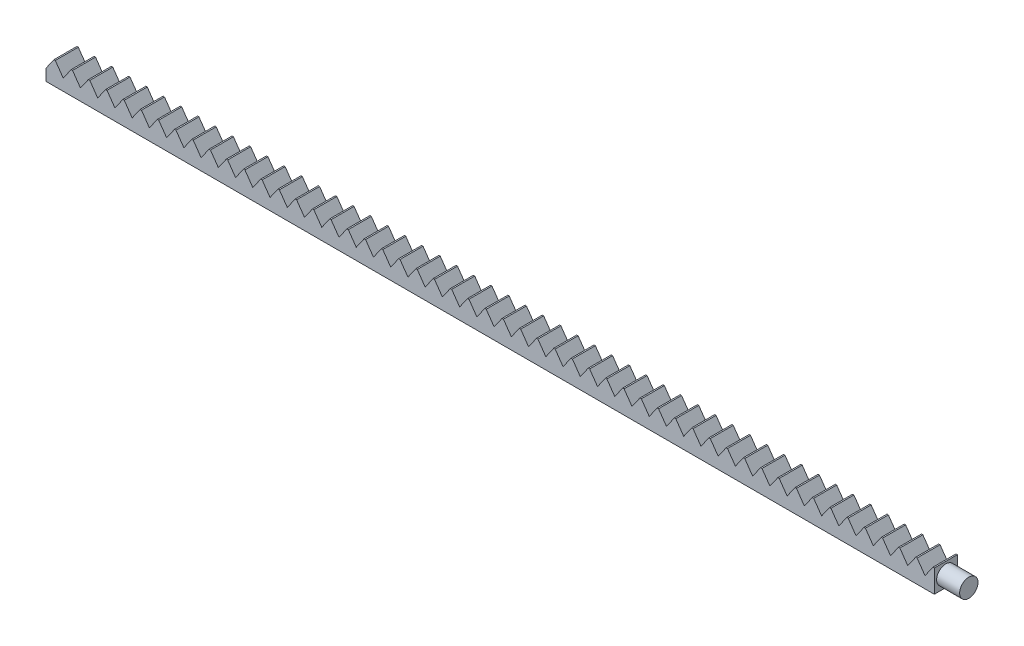
SolidWorks part; units mm, degrees
ref_plane "Front Plane" through (0, 0, 0) normal (0, 0, 1) x (1, 0, 0)
ref_plane "Top Plane" through (0, 0, 0) normal (0, 1, 0) x (1, 0, 0)
ref_plane "Right Plane" through (0, 0, 0) normal (1, 0, 0) x (0, 0, -1)
sketch "Sketch1" plane through (0, 0, 0) normal (0, 0, 1) x (1, 0, 0)
  line L1 (0, 0) -> (0, 6.35)
  line L2 (0, 6.35) -> (4.3815, 12.6074)
  line L3 (4.3815, 12.6074) -> (5.1435, 12.6074)
  line L4 (5.1435, 12.6074) -> (9.525, 6.35)
  line L5 (9.525, 6.35) -> (13.9065, 12.6074)
  line L6 (13.9065, 12.6074) -> (14.6685, 12.6074)
  line L7 (14.6685, 12.6074) -> (19.05, 6.35)
  line L8 (4.3815, 12.6074) -> (4.3815, -0.2019) construction
  line L9 (0, 6.35) -> (161.925, 6.35) construction
  line L10 (19.05, 6.35) -> (23.4315, 12.6074)
  line L11 (24.1935, 12.6074) -> (28.575, 6.35)
  line L12 (28.575, 6.35) -> (32.9565, 12.6074)
  line L13 (32.9565, 12.6074) -> (33.7185, 12.6074)
  line L14 (23.4315, 12.6074) -> (24.1935, 12.6074)
  line L15 (33.7185, 12.6074) -> (38.1, 6.35)
  line L16 (38.1, 6.35) -> (42.4815, 12.6074)
  line L17 (43.2435, 12.6074) -> (47.625, 6.35)
  line L18 (47.625, 6.35) -> (52.0065, 12.6074)
  line L19 (52.0065, 12.6074) -> (52.7685, 12.6074)
  line L20 (42.4815, 12.6074) -> (43.2435, 12.6074)
  line L21 (52.7685, 12.6074) -> (57.15, 6.35)
  line L22 (57.15, 6.35) -> (61.5315, 12.6074)
  line L23 (62.2935, 12.6074) -> (66.675, 6.35)
  line L24 (66.675, 6.35) -> (71.0565, 12.6074)
  line L25 (71.0565, 12.6074) -> (71.8185, 12.6074)
  line L26 (61.5315, 12.6074) -> (62.2935, 12.6074)
  line L27 (71.8185, 12.6074) -> (76.2, 6.35)
  line L28 (76.2, 6.35) -> (80.5815, 12.6074)
  line L29 (81.3435, 12.6074) -> (85.725, 6.35)
  line L30 (85.725, 6.35) -> (90.1065, 12.6074)
  line L31 (90.1065, 12.6074) -> (90.8685, 12.6074)
  line L32 (80.5815, 12.6074) -> (81.3435, 12.6074)
  line L33 (90.8685, 12.6074) -> (95.25, 6.35)
  line L34 (95.25, 6.35) -> (99.6315, 12.6074)
  line L35 (100.3935, 12.6074) -> (104.775, 6.35)
  line L36 (104.775, 6.35) -> (109.1565, 12.6074)
  line L37 (109.1565, 12.6074) -> (109.9185, 12.6074)
  line L38 (99.6315, 12.6074) -> (100.3935, 12.6074)
  line L39 (109.9185, 12.6074) -> (114.3, 6.35)
  line L40 (114.3, 6.35) -> (118.6815, 12.6074)
  line L41 (119.4435, 12.6074) -> (123.825, 6.35)
  line L42 (123.825, 6.35) -> (128.2065, 12.6074)
  line L43 (128.2065, 12.6074) -> (128.9685, 12.6074)
  line L44 (118.6815, 12.6074) -> (119.4435, 12.6074)
  line L45 (128.9685, 12.6074) -> (133.35, 6.35)
  line L46 (133.35, 6.35) -> (137.7315, 12.6074)
  line L47 (138.4935, 12.6074) -> (142.875, 6.35)
  line L48 (142.875, 6.35) -> (147.2565, 12.6074)
  line L49 (147.2565, 12.6074) -> (148.0185, 12.6074)
  line L50 (137.7315, 12.6074) -> (138.4935, 12.6074)
  line L51 (148.0185, 12.6074) -> (152.4, 6.35)
  line L52 (152.4, 6.35) -> (156.7815, 12.6074)
  line L53 (157.5435, 12.6074) -> (161.925, 6.35)
  line L54 (161.925, 6.35) -> (166.3065, 12.6074)
  line L55 (166.3065, 12.6074) -> (167.0685, 12.6074)
  line L56 (156.7815, 12.6074) -> (157.5435, 12.6074)
  line L57 (167.0685, 12.6074) -> (171.45, 6.35)
  line L58 (171.45, 6.35) -> (175.8315, 12.6074)
  line L59 (176.5935, 12.6074) -> (180.975, 6.35)
  line L60 (180.975, 6.35) -> (185.3565, 12.6074)
  line L61 (185.3565, 12.6074) -> (186.1185, 12.6074)
  line L62 (175.8315, 12.6074) -> (176.5935, 12.6074)
  line L63 (186.1185, 12.6074) -> (190.5, 6.35)
  line L64 (190.5, 6.35) -> (194.8815, 12.6074)
  line L65 (195.6435, 12.6074) -> (200.025, 6.35)
  line L66 (200.025, 6.35) -> (204.4065, 12.6074)
  line L67 (204.4065, 12.6074) -> (205.1685, 12.6074)
  line L68 (194.8815, 12.6074) -> (195.6435, 12.6074)
  line L69 (205.1685, 12.6074) -> (209.55, 6.35)
  line L70 (209.55, 6.35) -> (213.9315, 12.6074)
  line L71 (214.6935, 12.6074) -> (219.075, 6.35)
  line L72 (219.075, 6.35) -> (223.4565, 12.6074)
  line L73 (223.4565, 12.6074) -> (224.2185, 12.6074)
  line L74 (213.9315, 12.6074) -> (214.6935, 12.6074)
  line L75 (224.2185, 12.6074) -> (228.6, 6.35)
  line L76 (228.6, 6.35) -> (232.9815, 12.6074)
  line L77 (233.7435, 12.6074) -> (238.125, 6.35)
  line L78 (238.125, 6.35) -> (242.5065, 12.6074)
  line L79 (242.5065, 12.6074) -> (243.2685, 12.6074)
  line L80 (232.9815, 12.6074) -> (233.7435, 12.6074)
  line L81 (243.2685, 12.6074) -> (247.65, 6.35)
  line L82 (247.65, 6.35) -> (252.0315, 12.6074)
  line L83 (252.7935, 12.6074) -> (257.175, 6.35)
  line L84 (257.175, 6.35) -> (261.5565, 12.6074)
  line L85 (261.5565, 12.6074) -> (262.3185, 12.6074)
  line L86 (252.0315, 12.6074) -> (252.7935, 12.6074)
  line L87 (262.3185, 12.6074) -> (266.7, 6.35)
  line L88 (266.7, 6.35) -> (271.0815, 12.6074)
  line L89 (271.8435, 12.6074) -> (276.225, 6.35)
  line L90 (276.225, 6.35) -> (280.6065, 12.6074)
  line L91 (280.6065, 12.6074) -> (281.3685, 12.6074)
  line L92 (271.0815, 12.6074) -> (271.8435, 12.6074)
  line L93 (281.3685, 12.6074) -> (285.75, 6.35)
  line L94 (285.75, 6.35) -> (290.1315, 12.6074)
  line L95 (290.8935, 12.6074) -> (295.275, 6.35)
  line L96 (295.275, 6.35) -> (299.6565, 12.6074)
  line L97 (299.6565, 12.6074) -> (300.4185, 12.6074)
  line L98 (290.1315, 12.6074) -> (290.8935, 12.6074)
  line L99 (300.4185, 12.6074) -> (304.8, 6.35)
  line L100 (304.8, 6.35) -> (309.1815, 12.6074)
  line L101 (309.9435, 12.6074) -> (314.325, 6.35)
  line L102 (314.325, 6.35) -> (318.7065, 12.6074)
  line L103 (318.7065, 12.6074) -> (319.4685, 12.6074)
  line L104 (309.1815, 12.6074) -> (309.9435, 12.6074)
  line L105 (319.4685, 12.6074) -> (323.85, 6.35)
  line L106 (323.85, 6.35) -> (328.2315, 12.6074)
  line L107 (328.9935, 12.6074) -> (333.375, 6.35)
  line L108 (333.375, 6.35) -> (337.7565, 12.6074)
  line L109 (337.7565, 12.6074) -> (338.5185, 12.6074)
  line L110 (328.2315, 12.6074) -> (328.9935, 12.6074)
  line L111 (338.5185, 12.6074) -> (342.9, 6.35)
  line L112 (342.9, 6.35) -> (347.2815, 12.6074)
  line L113 (348.0435, 12.6074) -> (352.425, 6.35)
  line L114 (352.425, 6.35) -> (356.8065, 12.6074)
  line L115 (356.8065, 12.6074) -> (357.5685, 12.6074)
  line L116 (347.2815, 12.6074) -> (348.0435, 12.6074)
  line L117 (357.5685, 12.6074) -> (361.95, 6.35)
  line L118 (361.95, 6.35) -> (366.3315, 12.6074)
  line L119 (367.0935, 12.6074) -> (371.475, 6.35)
  line L120 (371.475, 6.35) -> (375.8565, 12.6074)
  line L121 (375.8565, 12.6074) -> (376.6185, 12.6074)
  line L122 (366.3315, 12.6074) -> (367.0935, 12.6074)
  line L123 (376.6185, 12.6074) -> (381, 6.35)
  line L124 (381, 6.35) -> (385.3815, 12.6074)
  line L125 (386.1435, 12.6074) -> (390.525, 6.35)
  line L126 (390.525, 6.35) -> (394.9065, 12.6074)
  line L127 (394.9065, 12.6074) -> (395.6685, 12.6074)
  line L128 (385.3815, 12.6074) -> (386.1435, 12.6074)
  line L129 (395.6685, 12.6074) -> (400.05, 6.35)
  line L130 (400.05, 6.35) -> (404.4315, 12.6074)
  line L131 (405.1935, 12.6074) -> (409.575, 6.35)
  line L132 (409.575, 6.35) -> (413.9565, 12.6074)
  line L133 (413.9565, 12.6074) -> (414.7185, 12.6074)
  line L134 (404.4315, 12.6074) -> (405.1935, 12.6074)
  line L135 (414.7185, 12.6074) -> (419.1, 6.35)
  line L136 (419.1, 6.35) -> (423.4815, 12.6074)
  line L137 (424.2435, 12.6074) -> (428.625, 6.35)
  line L138 (428.625, 6.35) -> (433.0065, 12.6074)
  line L139 (433.0065, 12.6074) -> (433.7685, 12.6074)
  line L140 (423.4815, 12.6074) -> (424.2435, 12.6074)
  line L141 (433.7685, 12.6074) -> (438.15, 6.35)
  line L142 (438.15, 6.35) -> (442.5315, 12.6074)
  line L143 (443.2935, 12.6074) -> (447.675, 6.35)
  line L144 (447.675, 6.35) -> (452.0565, 12.6074)
  line L145 (452.0565, 12.6074) -> (452.8185, 12.6074)
  line L146 (442.5315, 12.6074) -> (443.2935, 12.6074)
  line L147 (452.8185, 12.6074) -> (457.2, 6.35)
  line L148 (457.2, 6.35) -> (461.5815, 12.6074)
  line L149 (462.3435, 12.6074) -> (466.725, 6.35)
  line L150 (466.725, 6.35) -> (471.1065, 12.6074)
  line L151 (471.1065, 12.6074) -> (471.8685, 12.6074)
  line L152 (461.5815, 12.6074) -> (462.3435, 12.6074)
  line L153 (471.8685, 12.6074) -> (476.25, 6.35)
  line L154 (476.25, 6.35) -> (480.6315, 12.6074)
  line L155 (481.3935, 12.6074) -> (485.775, 6.35)
  line L156 (485.775, 6.35) -> (490.1565, 12.6074)
  line L157 (490.1565, 12.6074) -> (490.9185, 12.6074)
  line L158 (480.6315, 12.6074) -> (481.3935, 12.6074)
  line L159 (490.9185, 12.6074) -> (495.3, 6.35)
  line L160 (0, 0) -> (495.3, 0)
  line L161 (495.3, 0) -> (495.3, 6.35)
  dimension "D1" = 35
  dimension "D2" = 35
  dimension "D3" = 0.762
  dimension "D4" = 19.05
  dimension "D5" = 6.35
  dimension "D6" = 26
extrude "Boss-Extrude1" add sketch "Sketch1" along normal blind 12.7
sketch "Sketch2" plane through (0, 0, 12.7) normal (0, 0, 1) x (1, 0, 0)
  line L0 (490.9185, 12.6074) -> (490.9185, 0)
  line L1 (0, 0) -> (495.3, 0) construction
  line L2 (490.9185, 0) -> (495.3, 0)
  line L3 (495.3, 0) -> (495.3, 6.35) construction
  line L4 (495.3, 0) -> (495.3, 12.6074)
  line L5 (495.3, 12.6074) -> (490.9185, 12.6074)
extrude "Cut-Extrude1" cut sketch "Sketch2" against normal through all
sketch "Sketch3" plane through (490.9185, 0, 0) normal (1, 0, 0) x (0, 0, -1)
  line L5 (-12.7, 12.6074) -> (0, 0) construction
  line L6 (-12.7, 0) -> (0, 12.6074) construction
  circle A0 centre (-6.35, 6.3037) radius 5.08
  point P4 (-6.35, 6.3037)
  dimension "D1" = 10.16
extrude "Boss-Extrude2" add sketch "Sketch3" along normal blind 12.7
